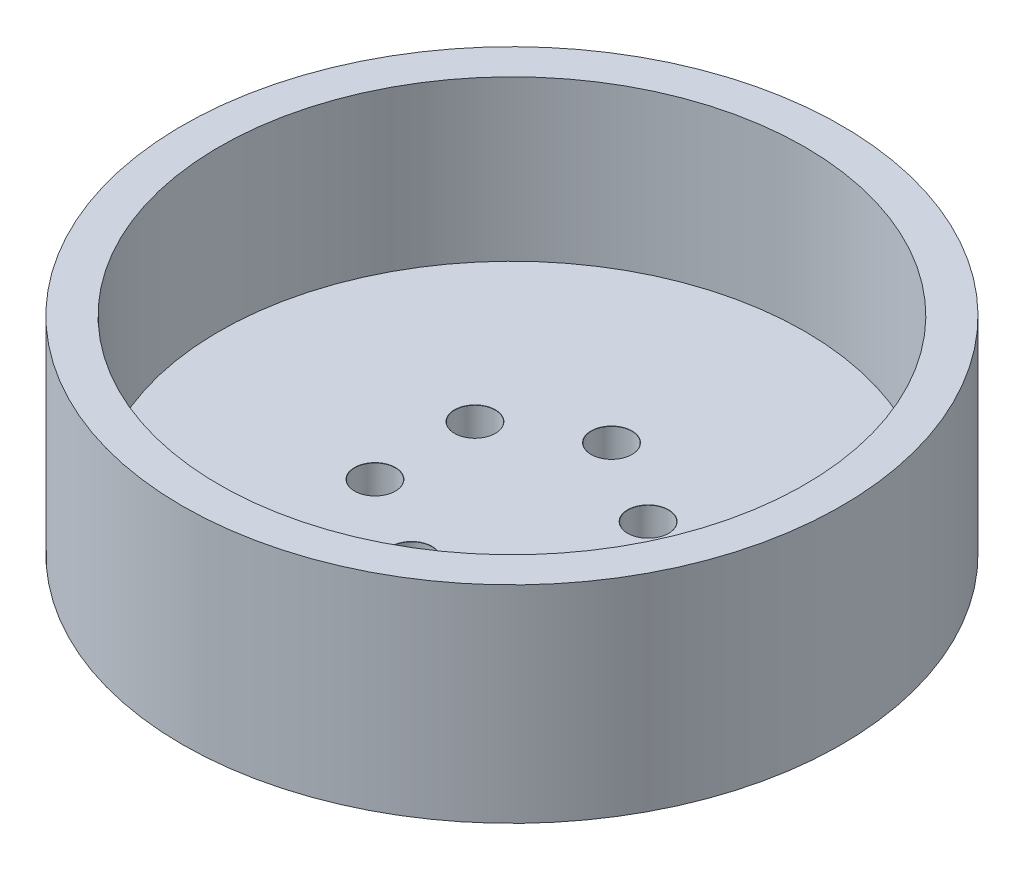
SolidWorks part; units mm, degrees
material "ABS"
ref_plane "Front Plane" through (0, 0, 0) normal (0, 0, 1) x (1, 0, 0)
ref_plane "Top Plane" through (0, 0, 0) normal (0, 1, 0) x (1, 0, 0)
ref_plane "Right Plane" through (0, 0, 0) normal (1, 0, 0) x (0, 0, -1)
sketch "Sketch1" plane through (0, 0, 0) normal (0, 1, 0) x (1, 0, 0)
  circle A0 centre (0, 0) radius 44.675
  dimension "D1" = 89.35
extrude "Boss-Extrude2" add sketch "Sketch1" along normal blind 6.35
sketch "Sketch6" plane through (0, 6.35, 0) normal (0, 1, 0) x (1, 0, 0)
  line L0 (0, 0) -> (0, 13.5)
hole_wizard "M5 Clearance Hole2" positions "Sketch7" profile "Sketch8" hole size "M5" standard "ANSI Metric" end condition through all
sketch "Sketch7" plane through (0, 6.35, 0) normal (0, 1, 0) x (1, 0, 0)
  point P0 (0, 13.5)
sketch "Sketch8" plane through (0, 6.35, -13.5) normal (1, 0, 0) x (0, 0, 1)
  line L0 (0, 0) -> (0, 6.35)
  line L1 (0, 6.35) -> (2.75, 6.35)
  line L2 (2.75, 6.35) -> (2.75, 0.025)
  line L3 (2.75, 0.025) -> (2.775, 0)
  line L5 (2.775, 0) -> (0, 0)
  line L6 (-2.75, 0.025) -> (-2.775, 0) construction
  line L11 (0, -6.35) -> (0, 107.95) construction
  dimension "Thru Hole Dia." = 5.5
  dimension "Thru Hole Depth" = 6.35
  dimension "Near C'Sink Dia." = 5.55
  dimension "Near C'Sink Angle" = 90
pattern_circular "CirPattern1" count 6 over 360 about axis through (0, 0, 0.0523) along (0, 1, 0) of "M5 Clearance Hole2"
sketch "Sketch13" plane through (0, 6.35, 0) normal (0, 1, 0) x (1, 0, 0)
  circle A3 centre (0, 0) radius 39.675
extrude "Boss-Extrude4" add sketch "Sketch13" along normal blind 21.65
